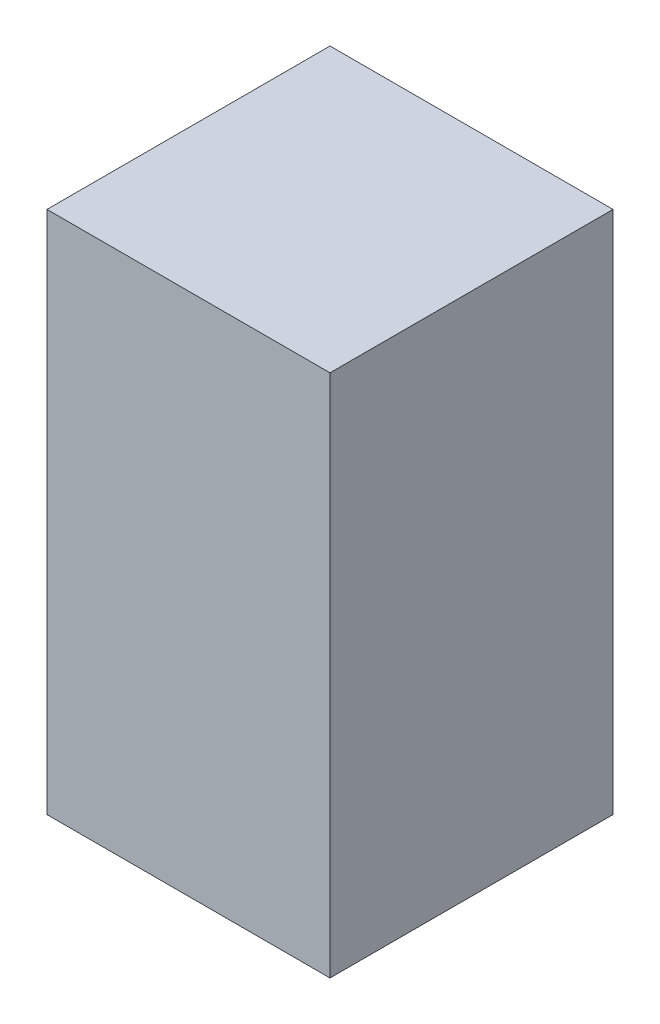
SolidWorks part; units mm, degrees
ref_plane "Front Plane" through (0, 0, 0) normal (0, 0, 1) x (1, 0, 0)
ref_plane "Top Plane" through (0, 0, 0) normal (0, 1, 0) x (1, 0, 0)
ref_plane "Right Plane" through (0, 0, 0) normal (1, 0, 0) x (0, 0, -1)
sketch "Sketch2" plane through (0, 0, 0) normal (0, 1, 0) x (1, 0, 0)
  line L1 (0, 0) -> (270, 0)
  line L2 (0, 0) -> (0, 270)
  line L3 (0, 270) -> (270, 270)
  line L4 (270, 0) -> (270, 270)
  dimension "D1" = 270
  dimension "D2" = 270
extrude "Boss-Extrude1" add sketch "Sketch2" along normal blind 500
sketch "Sketch4" plane through (0, 500, 0) normal (0, 1, 0) x (1, 0, 0)
  line L1 (0, 0) -> (270, 0)
  line L2 (0, 0) -> (0, 270)
  line L3 (0, 270) -> (270, 270)
  line L4 (270, 0) -> (270, 270)
  line L7 (270, 255) -> (255, 255)
  line L8 (255, 270) -> (255, 255)
  line L9 (255, 255) -> (15, 255)
  line L10 (255, 255) -> (255, 15)
  line L11 (255, 15) -> (15, 15)
  line L12 (15, 255) -> (15, 15)
  dimension "D1" = 15
  dimension "D2" = 15
  dimension "D3" = 240
  dimension "D4" = 240
